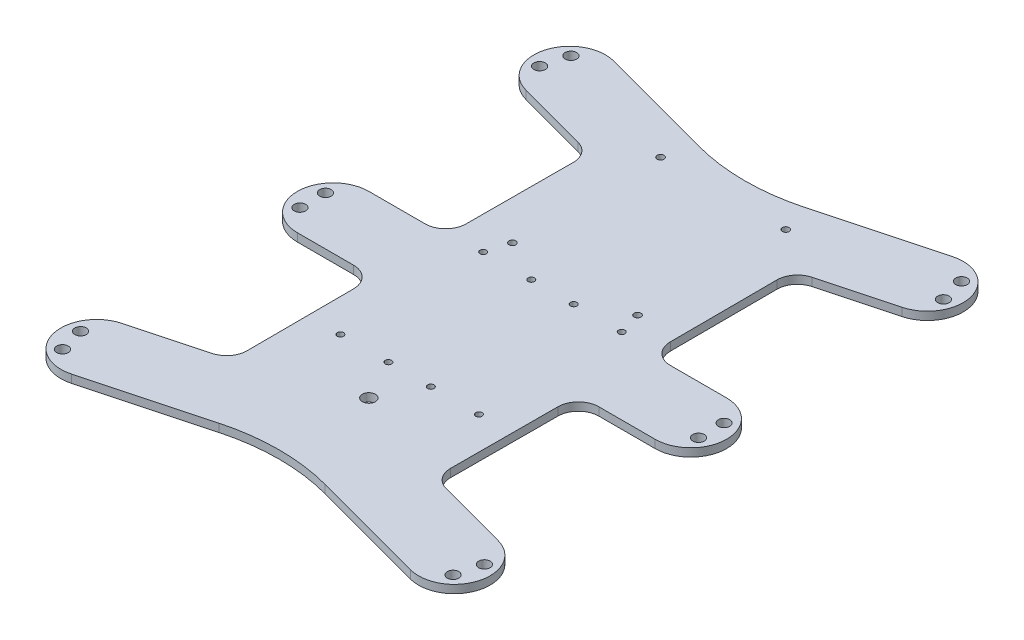
SolidWorks part; units mm, degrees
ref_plane "Front Plane" through (0, 0, 0) normal (0, 0, 1) x (1, 0, 0)
ref_plane "Top Plane" through (0, 0, 0) normal (0, 1, 0) x (1, 0, 0)
ref_plane "Right Plane" through (0, 0, 0) normal (1, 0, 0) x (0, 0, -1)
sketch "Sketch1" plane through (0, 0, 0) normal (0, 1, 0) x (1, 0, 0)
  line L0 (0, 32.1883) -> (0, -21.4181) construction
  line L1 (0, 0) -> (27.1703, 0) construction
  line L2 (-70, 14) -> (-40, 14)
  line L3 (-40, 14) -> (-39.8161, 70)
  line L4 (-39.8161, 70) -> (-73.6235, 79.0587)
  line L5 (-66.3765, 106.1046) -> (0, 88.3191)
  line L10 (-66.3765, 106.1046) -> (-73.6235, 79.0587) construction
  line L12 (-70, 14) -> (-70, -14) construction
  line L14 (-66.3765, -106.1046) -> (0, -88.3191)
  line L15 (-39.8161, -70) -> (-73.6235, -79.0587)
  line L16 (-40, -14) -> (-39.8161, -70)
  line L17 (-70, -14) -> (-40, -14)
  line L18 (66.3765, -106.1046) -> (0, -88.3191)
  line L19 (66.3765, 106.1046) -> (0, 88.3191)
  line L20 (70, 14) -> (70, -14) construction
  line L21 (66.3765, 106.1046) -> (73.6235, 79.0587) construction
  line L22 (70, -14) -> (40, -14)
  line L23 (40, -14) -> (39.8161, -70)
  line L24 (39.8161, -70) -> (73.6235, -79.0587)
  line L25 (39.8161, 70) -> (73.6235, 79.0587)
  line L26 (40, 14) -> (39.8161, 70)
  line L27 (70, 14) -> (40, 14)
  arc A0 (-70, 14) -> (-70, -14) centre (-70, 0) ccw
  arc A1 (-66.3765, 106.1046) -> (-73.6235, 79.0587) centre (-70, 92.5816) ccw
  arc A11 (-66.3765, -106.1046) -> (-73.6235, -79.0587) centre (-70, -92.5816) cw
  arc A18 (66.3765, -106.1046) -> (73.6235, -79.0587) centre (70, -92.5816) ccw
  arc A22 (66.3765, 106.1046) -> (73.6235, 79.0587) centre (70, 92.5816) cw
  arc A23 (70, 14) -> (70, -14) centre (70, 0) cw
  point P118 (-83.523, 96.2051)
  dimension "D2" = 14
  dimension "D3" = 70
  dimension "D1" = 75
  dimension "D5" = 30
  dimension "D6" = 35
  dimension "D7" = 56
extrude "Boss-Extrude1" add sketch "Sketch1" along normal blind 3.175
fillet "Fillet1" radius 80 2 edges at (0, 1.5875, -88.3191) (0, 1.5875, 88.3191)
fillet "Fillet2" radius 8 8 edges at (39.8161, 1.5875, 70) (40, 1.5875, 14) (40, 1.5875, -14) (39.8161, 1.5875, -70) (-39.8161, 1.5875, -70) (-40, 1.5875, -14) (-40, 1.5875, 14) (-39.8161, 1.5875, 70)
sketch "Sketch2" plane through (0, 3.175, 0) normal (0, 1, 0) x (1, 0, 0)
  circle A0 centre (-24.5, 24.6411) radius 1.35 construction
  circle A1 centre (24.5, 24.6411) radius 1.35 construction
  circle A2 centre (24.5, 82.6411) radius 1.35 construction
  circle A3 centre (-24.5, 82.6411) radius 1.35 construction
  circle A4 centre (-24.5, 24.6411) radius 1.35
  circle A5 centre (24.5, 24.6411) radius 1.35
  circle A6 centre (24.5, 82.6411) radius 1.35
  circle A7 centre (-24.5, 82.6411) radius 1.35
extrude "Cut-Extrude1" cut sketch "Sketch2" against normal through all
sketch "Sketch3" plane through (0, 3.175, 0) normal (0, 1, 0) x (1, 0, 0)
  circle A0 centre (-8.3, -40.0589) radius 1.25 construction
  circle A1 centre (-27.1, -40.0589) radius 1.25 construction
  circle A2 centre (-27.1, 15.8411) radius 1.25 construction
  circle A3 centre (-8.3, 15.8411) radius 1.25 construction
  circle A4 centre (8.3, 15.8411) radius 1.25 construction
  circle A5 centre (27.1, 15.8411) radius 1.25 construction
  circle A6 centre (8.3, -40.0589) radius 1.25 construction
  circle A7 centre (27.1, -40.0589) radius 1.25 construction
  circle A8 centre (-8.3, -40.0589) radius 1.25
  circle A9 centre (-27.1, -40.0589) radius 1.25
  circle A10 centre (-27.1, 15.8411) radius 1.25
  circle A11 centre (-8.3, 15.8411) radius 1.25
  circle A12 centre (8.3, 15.8411) radius 1.25
  circle A13 centre (27.1, 15.8411) radius 1.25
  circle A14 centre (8.3, -40.0589) radius 1.25
  circle A15 centre (27.1, -40.0589) radius 1.25
extrude "Cut-Extrude2" cut sketch "Sketch3" against normal through all
sketch "Sketch5" plane through (0, 3.175, 0) normal (0, 1, 0) x (1, 0, 0)
  line L0 (-39.862, -56.0189) -> (39.862, -56.0189) construction
  line L1 (-39.9738, -21.9737) -> (-39.8363, -63.8405) construction
  line L2 (39.8363, -63.8405) -> (39.9738, -21.9737) construction
  line L3 (-27.1, -43.3589) -> (-8.3, -43.3589) construction
  circle A0 centre (0, -56.0189) radius 2.55
  point P6 (0, -56.0189)
  dimension "D2" = 5.1
  dimension "D1" = 12.66
extrude "Cut-Extrude3" cut sketch "Sketch5" against normal through all
sketch "Sketch7" plane through (0, 3.175, 0) normal (0, 1, 0) x (1, 0, 0)
  circle A0 centre (-76.4333, -99.4818) radius 2.25 construction
  circle A1 centre (-79.0215, -89.8226) radius 2.25 construction
  circle A2 centre (-78, -5) radius 2.25 construction
  circle A3 centre (-78, 5) radius 2.25 construction
  circle A4 centre (-79.0215, 89.8226) radius 2.25 construction
  circle A5 centre (-76.4333, 99.4818) radius 2.25 construction
  circle A6 centre (79.0215, 89.8226) radius 2.25 construction
  circle A7 centre (76.4333, 99.4818) radius 2.25 construction
  circle A8 centre (78, -5) radius 2.25 construction
  circle A9 centre (78, 5) radius 2.25 construction
  circle A10 centre (79.0215, -89.8226) radius 2.25 construction
  circle A11 centre (76.4333, -99.4818) radius 2.25 construction
  circle A12 centre (-76.4333, -99.4818) radius 2.25
  circle A13 centre (-79.0215, -89.8226) radius 2.25
  circle A14 centre (-78, -5) radius 2.25
  circle A15 centre (-78, 5) radius 2.25
  circle A16 centre (-79.0215, 89.8226) radius 2.25
  circle A17 centre (-76.4333, 99.4818) radius 2.25
  circle A18 centre (79.0215, 89.8226) radius 2.25
  circle A19 centre (76.4333, 99.4818) radius 2.25
  circle A20 centre (78, -5) radius 2.25
  circle A21 centre (78, 5) radius 2.25
  circle A22 centre (79.0215, -89.8226) radius 2.25
  circle A23 centre (76.4333, -99.4818) radius 2.25
extrude "Cut-Extrude4" cut sketch "Sketch7" against normal blind 10
